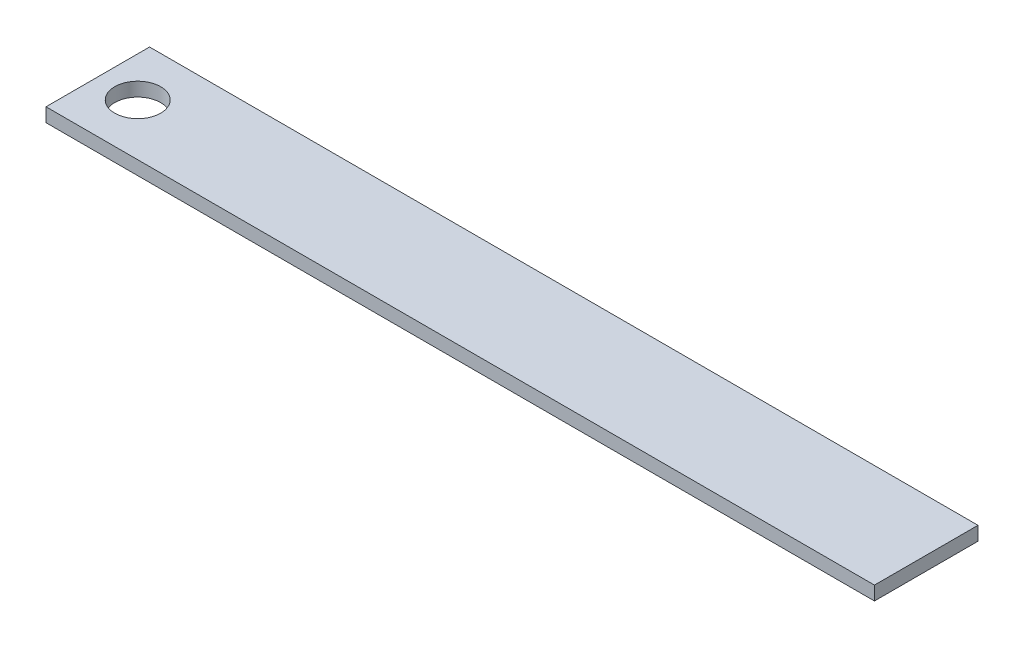
SolidWorks part; units mm, degrees
ref_plane "Front" through (0, 0, 0) normal (0, 0, 1) x (1, 0, 0)
ref_plane "Top" through (0, 0, 0) normal (0, 1, 0) x (1, 0, 0)
ref_plane "Right" through (0, 0, 0) normal (1, 0, 0) x (0, 0, -1)
sketch "Sketch1" plane through (0, 0, 0) normal (0, 1, 0) x (1, 0, 0)
  line L0 (60, -7.5) -> (-60, -7.5)
  line L1 (60, -7.5) -> (60, 7.5)
  line L2 (-60, -7.5) -> (-60, 7.5)
  line L3 (60, 7.5) -> (-60, 7.5)
  line L4 (60, -7.5) -> (-60, 7.5) construction
  line L5 (-60, -7.5) -> (60, 7.5) construction
  circle A0 centre (-54.2175, 0) radius 3.3276
  point P1 (0, 0)
  point P3 (-54.2175, 0)
  dimension "D1" = 120
  dimension "D2" = 15
extrude "Boss-Extrude1" add sketch "Sketch1" along normal blind 2
